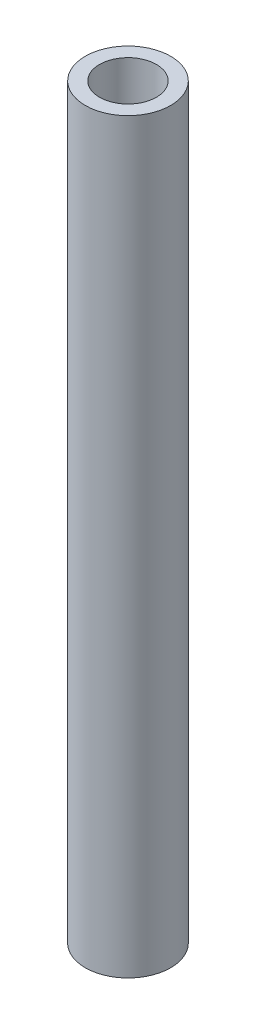
SolidWorks part; units mm, degrees
ref_plane "Front Plane" through (0, 0, 0) normal (0, 0, 1) x (1, 0, 0)
ref_plane "Top Plane" through (0, 0, 0) normal (0, 1, 0) x (1, 0, 0)
ref_plane "Right Plane" through (0, 0, 0) normal (1, 0, 0) x (0, 0, -1)
sketch "Sketch1" plane through (0, 0, 0) normal (0, 1, 0) x (1, 0, 0)
  circle A0 centre (0, 0) radius 2
  circle A1 centre (0, 0) radius 3
  dimension "D1" = 4
  dimension "D2" = 1
extrude "Boss-Extrude1" add sketch "Sketch1" along normal blind 52.5
